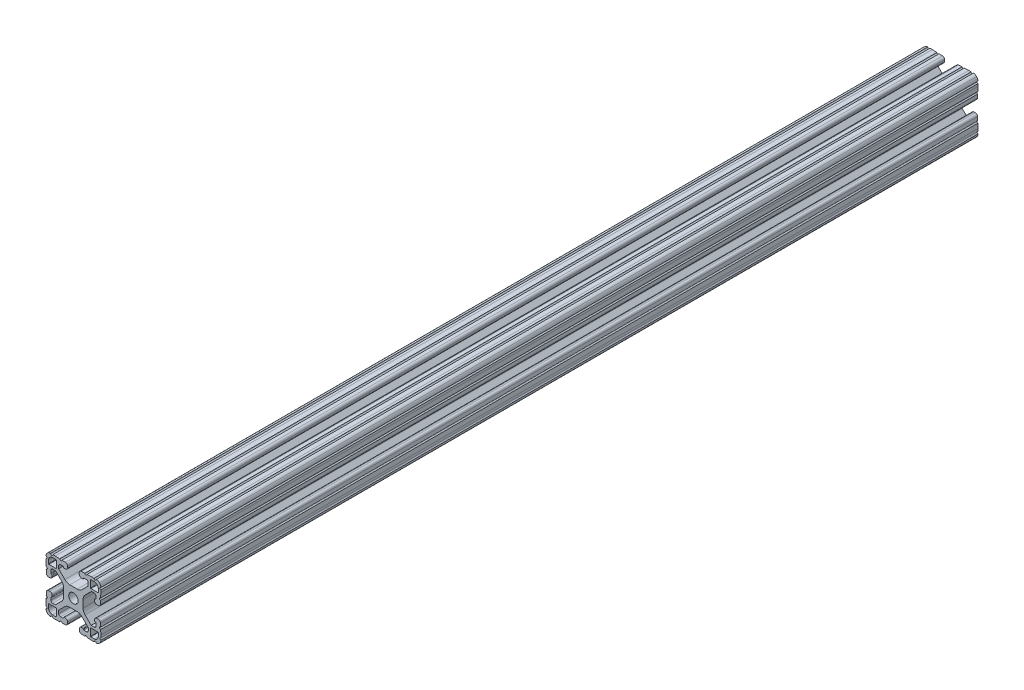
SolidWorks part; units mm, degrees
ref_plane "Front Plane" through (0, 0, 0) normal (0, 0, 1) x (1, 0, 0)
ref_plane "Top Plane" through (0, 0, 0) normal (0, 1, 0) x (1, 0, 0)
ref_plane "Right Plane" through (0, 0, 0) normal (1, 0, 0) x (0, 0, -1)
ref_plane "Plane1" through (0, 0, -25.4) normal (0, 0, -1) x (-1, 0, 0)
sketch "Sketch1" plane through (0, 0, -25.4) normal (0, 0, -1) x (-1, 0, 0)
  line L0 (-83.3577, 88.2941) -> (-83.3577, 93.1709)
  line L1 (-83.1037, 93.4249) -> (-80.767, 93.4249)
  line L2 (-77.9729, 90.6309) -> (-77.9729, 88.2941)
  line L3 (-78.2269, 88.0401) -> (-83.1037, 88.0401)
  line L4 (-83.3577, 59.2291) -> (-83.3577, 64.1059)
  line L5 (-83.1037, 64.3599) -> (-78.2269, 64.3599)
  line L6 (-77.9729, 64.1059) -> (-77.9729, 61.7691)
  line L7 (-80.767, 58.9751) -> (-83.1037, 58.9751)
  line L8 (-107.1423, 93.1709) -> (-107.1423, 88.2941)
  line L9 (-107.3963, 88.0401) -> (-112.2731, 88.0401)
  line L10 (-112.5271, 88.2941) -> (-112.5271, 90.6309)
  line L11 (-109.733, 93.4249) -> (-107.3963, 93.4249)
  line L12 (-107.1423, 64.1059) -> (-107.1423, 59.2291)
  line L13 (-107.3963, 58.9751) -> (-109.733, 58.9751)
  line L14 (-112.5271, 61.7691) -> (-112.5271, 64.1059)
  line L15 (-112.2731, 64.3599) -> (-107.3963, 64.3599)
  line L16 (-88.0437, 91.8626) -> (-86.2967, 91.9236)
  line L17 (-84.9824, 90.6544) -> (-84.9824, 88.8002)
  line L18 (-84.9824, 88.8002) -> (-89.3066, 84.476)
  line L19 (-92.7196, 83.0295) -> (-97.9616, 83.0295)
  line L20 (-101.3202, 84.4207) -> (-105.516, 88.6165)
  line L21 (-105.516, 88.6165) -> (-105.516, 90.7313)
  line L22 (-104.2017, 92.0006) -> (-102.4547, 91.9396)
  line L23 (-101.7262, 91.1059) -> (-100.9297, 91.0781)
  line L24 (-99.2999, 92.6519) -> (-99.2999, 93.5668)
  line L25 (-100.8197, 95.1407) -> (-103.2119, 95.2242)
  line L26 (-104.735, 95.2774) -> (-107.9359, 95.3892)
  line L27 (-107.9359, 95.3892) -> (-109.5615, 95.3892)
  line L28 (-114.2859, 90.6648) -> (-114.2859, 89.0392)
  line L29 (-114.2859, 89.0392) -> (-114.1741, 85.8383)
  line L30 (-114.1209, 84.3152) -> (-114.0374, 81.9231)
  line L31 (-112.4635, 80.4032) -> (-111.5486, 80.4032)
  line L32 (-109.9748, 82.033) -> (-110.0026, 82.8295)
  line L33 (-110.8377, 83.5577) -> (-110.8987, 85.3047)
  line L34 (-109.6294, 86.619) -> (-107.8072, 86.619)
  line L35 (-107.8072, 86.619) -> (-103.3649, 82.1768)
  line L36 (-101.9737, 78.8182) -> (-101.9737, 73.576)
  line L37 (-103.3649, 70.2174) -> (-107.5607, 66.0217)
  line L38 (-107.5607, 66.0217) -> (-109.6524, 66.0217)
  line L39 (-110.9217, 67.336) -> (-110.8607, 69.083)
  line L40 (-110.0322, 69.8124) -> (-110.0043, 70.6089)
  line L41 (-111.5782, 72.2387) -> (-112.4931, 72.2387)
  line L42 (-114.0669, 70.7189) -> (-114.1505, 68.3267)
  line L43 (-114.2036, 66.8036) -> (-114.3154, 63.6027)
  line L44 (-114.3154, 63.6027) -> (-114.3154, 61.9626)
  line L45 (-109.6111, 57.1437) -> (-107.9855, 57.1437)
  line L46 (-107.9855, 57.1437) -> (-104.7846, 57.2555)
  line L47 (-103.2615, 57.3086) -> (-100.8694, 57.3922)
  line L48 (-99.3495, 58.966) -> (-99.3495, 59.8809)
  line L49 (-100.9794, 61.4548) -> (-101.7758, 61.4269)
  line L50 (-102.5054, 60.599) -> (-104.2524, 60.538)
  line L51 (-105.5667, 61.8072) -> (-105.5667, 63.6295)
  line L52 (-105.5667, 63.6295) -> (-101.1311, 68.065)
  line L53 (-97.7725, 69.4562) -> (-92.5304, 69.4562)
  line L54 (-89.1717, 68.065) -> (-84.976, 63.8692)
  line L55 (-84.976, 63.8692) -> (-84.976, 61.7811)
  line L56 (-86.2903, 60.5118) -> (-88.0373, 60.5728)
  line L57 (-88.7596, 61.4332) -> (-89.5561, 61.461)
  line L58 (-91.1859, 59.8872) -> (-91.1859, 58.9723)
  line L59 (-89.6661, 57.3985) -> (-87.2739, 57.3149)
  line L60 (-85.7508, 57.2617) -> (-82.5499, 57.15)
  line L61 (-82.5499, 57.15) -> (-80.9244, 57.15)
  line L62 (-76.2, 61.8744) -> (-76.2, 63.4999)
  line L63 (-76.2, 63.4999) -> (-76.3117, 66.7008)
  line L64 (-76.3649, 68.2239) -> (-76.4484, 70.6161)
  line L65 (-78.0223, 72.1359) -> (-78.9372, 72.1359)
  line L66 (-80.511, 70.5061) -> (-80.4832, 69.7096)
  line L67 (-79.6552, 68.9801) -> (-79.5942, 67.2331)
  line L68 (-80.8634, 65.9188) -> (-82.6857, 65.9188)
  line L69 (-82.6857, 65.9188) -> (-87.1213, 70.3543)
  line L70 (-88.5125, 73.7128) -> (-88.5126, 78.955)
  line L71 (-87.1214, 82.3137) -> (-82.9257, 86.5095)
  line L72 (-82.9257, 86.5095) -> (-80.8375, 86.5095)
  line L73 (-79.5682, 85.1951) -> (-79.6293, 83.4482)
  line L74 (-80.4896, 82.7258) -> (-80.5175, 81.9294)
  line L75 (-78.9436, 80.2995) -> (-78.0287, 80.2995)
  line L76 (-76.4549, 81.8194) -> (-76.3713, 84.2115)
  line L77 (-76.3182, 85.7346) -> (-76.2064, 88.9355)
  line L78 (-76.2064, 88.9355) -> (-76.2064, 90.5611)
  line L79 (-80.9308, 95.2855) -> (-82.5564, 95.2855)
  line L80 (-82.5564, 95.2855) -> (-85.7573, 95.1737)
  line L81 (-87.2803, 95.1205) -> (-89.6725, 95.037)
  line L82 (-91.1924, 93.4632) -> (-91.1924, 92.5483)
  line L83 (-89.5625, 90.9744) -> (-88.7661, 91.0023)
  arc A0 (-83.3577, 93.1709) -> (-83.1037, 93.4249) centre (-83.1037, 93.1709) cw
  arc A1 (-80.767, 93.4249) -> (-77.9729, 90.6309) centre (-80.7669, 90.6309) cw
  arc A2 (-77.9729, 88.2941) -> (-78.2269, 88.0401) centre (-78.2269, 88.2941) cw
  arc A3 (-83.1037, 88.0401) -> (-83.3577, 88.2941) centre (-83.1037, 88.2941) cw
  arc A4 (-83.1037, 58.9751) -> (-83.3577, 59.2291) centre (-83.1037, 59.2291) cw
  arc A5 (-83.3577, 64.1059) -> (-83.1037, 64.3599) centre (-83.1037, 64.1059) cw
  arc A6 (-78.2269, 64.3599) -> (-77.9729, 64.1059) centre (-78.2269, 64.1059) cw
  arc A7 (-77.9729, 61.7691) -> (-80.767, 58.9751) centre (-80.7669, 61.7691) cw
  arc A8 (-107.3963, 93.4249) -> (-107.1423, 93.1709) centre (-107.3963, 93.1709) cw
  arc A9 (-107.1423, 88.2941) -> (-107.3963, 88.0401) centre (-107.3963, 88.2941) cw
  arc A10 (-112.2731, 88.0401) -> (-112.5271, 88.2941) centre (-112.2731, 88.2941) cw
  arc A11 (-112.5271, 90.6309) -> (-109.733, 93.4249) centre (-109.7331, 90.6309) cw
  arc A12 (-107.1423, 59.2291) -> (-107.3963, 58.9751) centre (-107.3963, 59.2291) cw
  arc A13 (-109.733, 58.9751) -> (-112.5271, 61.7691) centre (-109.7331, 61.7691) cw
  arc A14 (-112.5271, 64.1059) -> (-112.2731, 64.3599) centre (-112.2731, 64.1059) cw
  arc A15 (-107.3963, 64.3599) -> (-107.1423, 64.1059) centre (-107.3963, 64.1059) cw
  circle A16 centre (-95.25, 76.2) radius 3.2639
  arc A17 (-88.7661, 91.0023) -> (-88.3984, 91.383) centre (-88.7794, 91.383) ccw
  arc A18 (-88.3984, 91.383) -> (-88.0437, 91.8626) centre (-88.0304, 91.4819) cw
  arc A19 (-86.2967, 91.9236) -> (-84.9824, 90.6544) centre (-86.2524, 90.6544) cw
  arc A20 (-89.3066, 84.476) -> (-92.7196, 83.0295) centre (-92.7196, 87.7793) cw
  arc A21 (-97.9616, 83.0295) -> (-101.3202, 84.4207) centre (-97.9616, 87.7793) cw
  arc A22 (-105.516, 90.7313) -> (-104.2017, 92.0006) centre (-104.246, 90.7313) cw
  arc A23 (-102.4547, 91.9396) -> (-102.087, 91.5588) centre (-102.468, 91.5588) cw
  arc A24 (-102.087, 91.5588) -> (-101.7262, 91.1059) centre (-101.7129, 91.4867) ccw
  arc A25 (-100.9297, 91.0781) -> (-99.2999, 92.6519) centre (-100.8747, 92.6519) ccw
  arc A26 (-99.2999, 93.5668) -> (-100.8197, 95.1407) centre (-100.8747, 93.5668) ccw
  arc A27 (-103.2119, 95.2242) -> (-104.735, 95.2774) centre (-103.9735, 95.2508) cw
  arc A28 (-109.5615, 95.3892) -> (-111.0855, 95.3892) centre (-110.3235, 95.3892) cw
  arc A29 (-111.0855, 95.3892) -> (-113.3432, 94.4465) centre (-111.0855, 92.2142) ccw
  arc A30 (-113.3432, 94.4465) -> (-114.2859, 92.1888) centre (-111.1109, 92.1888) ccw
  arc A31 (-114.2859, 92.1888) -> (-114.2859, 90.6648) centre (-114.2859, 91.4268) cw
  arc A32 (-114.1741, 85.8383) -> (-114.1209, 84.3152) centre (-114.1475, 85.0768) cw
  arc A33 (-114.0374, 81.9231) -> (-112.4635, 80.4032) centre (-112.4635, 81.978) ccw
  arc A34 (-111.5486, 80.4032) -> (-109.9748, 82.033) centre (-111.5486, 81.978) ccw
  arc A35 (-110.0026, 82.8295) -> (-110.3834, 83.1972) centre (-110.3834, 82.8162) ccw
  arc A36 (-110.3834, 83.1972) -> (-110.8377, 83.5577) centre (-110.4569, 83.571) cw
  arc A37 (-110.8987, 85.3047) -> (-109.6294, 86.619) centre (-109.6294, 85.349) cw
  arc A38 (-103.3649, 82.1768) -> (-101.9737, 78.8182) centre (-106.7235, 78.8182) cw
  arc A39 (-101.9737, 73.576) -> (-103.3649, 70.2174) centre (-106.7235, 73.576) cw
  arc A40 (-109.6524, 66.0217) -> (-110.9217, 67.336) centre (-109.6524, 67.2917) cw
  arc A41 (-110.8607, 69.083) -> (-110.4799, 69.4507) centre (-110.4799, 69.0697) cw
  arc A42 (-110.4799, 69.4507) -> (-110.0322, 69.8124) centre (-110.413, 69.8257) ccw
  arc A43 (-110.0043, 70.6089) -> (-111.5782, 72.2387) centre (-111.5782, 70.6639) ccw
  arc A44 (-112.4931, 72.2387) -> (-114.0669, 70.7189) centre (-112.4931, 70.6639) ccw
  arc A45 (-114.1505, 68.3267) -> (-114.2036, 66.8036) centre (-114.1771, 67.5652) cw
  arc A46 (-114.3154, 61.9626) -> (-114.3332, 60.4644) centre (-114.4639, 61.2152) cw
  arc A47 (-114.3332, 60.4644) -> (-113.3928, 58.0864) centre (-111.1605, 60.3441) ccw
  arc A48 (-113.3928, 58.0864) -> (-111.1351, 57.1437) centre (-111.1351, 60.3187) ccw
  arc A49 (-111.1351, 57.1437) -> (-109.6111, 57.1437) centre (-110.3731, 57.1437) cw
  arc A50 (-104.7846, 57.2555) -> (-103.2615, 57.3086) centre (-104.0231, 57.2821) cw
  arc A51 (-100.8694, 57.3922) -> (-99.3495, 58.966) centre (-100.9243, 58.966) ccw
  arc A52 (-99.3495, 59.8809) -> (-100.9794, 61.4548) centre (-100.9243, 59.8809) ccw
  arc A53 (-101.7758, 61.4269) -> (-102.1435, 61.0462) centre (-101.7625, 61.0462) ccw
  arc A54 (-102.1435, 61.0462) -> (-102.5054, 60.599) centre (-102.5187, 60.9797) cw
  arc A55 (-104.2524, 60.538) -> (-105.5667, 61.8072) centre (-104.2967, 61.8072) cw
  arc A56 (-101.1311, 68.065) -> (-97.7725, 69.4562) centre (-97.7725, 64.7064) cw
  arc A57 (-92.5304, 69.4562) -> (-89.1717, 68.065) centre (-92.5304, 64.7064) cw
  arc A58 (-84.976, 61.7811) -> (-86.2903, 60.5118) centre (-86.246, 61.7811) cw
  arc A59 (-88.0373, 60.5728) -> (-88.405, 60.9536) centre (-88.024, 60.9536) cw
  arc A60 (-88.405, 60.9536) -> (-88.7596, 61.4332) centre (-88.7729, 61.0524) ccw
  arc A61 (-89.5561, 61.461) -> (-91.1859, 59.8872) centre (-89.6111, 59.8872) ccw
  arc A62 (-91.1859, 58.9723) -> (-89.6661, 57.3985) centre (-89.6111, 58.9723) ccw
  arc A63 (-87.2739, 57.3149) -> (-85.7508, 57.2617) centre (-86.5124, 57.2883) cw
  arc A64 (-80.9244, 57.15) -> (-79.4004, 57.15) centre (-80.1624, 57.15) cw
  arc A65 (-79.4004, 57.15) -> (-77.1426, 58.0927) centre (-79.4004, 60.325) ccw
  arc A66 (-77.1426, 58.0927) -> (-76.2, 60.3504) centre (-79.375, 60.3504) ccw
  arc A67 (-76.2, 60.3504) -> (-76.2, 61.8744) centre (-76.2, 61.1124) cw
  arc A68 (-76.3117, 66.7008) -> (-76.3649, 68.2239) centre (-76.3383, 67.4624) cw
  arc A69 (-76.4484, 70.6161) -> (-78.0223, 72.1359) centre (-78.0223, 70.5611) ccw
  arc A70 (-78.9372, 72.1359) -> (-80.511, 70.5061) centre (-78.9372, 70.5611) ccw
  arc A71 (-80.4832, 69.7096) -> (-80.1024, 69.342) centre (-80.1024, 69.723) ccw
  arc A72 (-80.1024, 69.342) -> (-79.6552, 68.9801) centre (-80.036, 68.9668) cw
  arc A73 (-79.5942, 67.2331) -> (-80.8634, 65.9188) centre (-80.8634, 67.1888) cw
  arc A74 (-87.1213, 70.3543) -> (-88.5125, 73.7128) centre (-83.7627, 73.7129) cw
  arc A75 (-88.5126, 78.955) -> (-87.1214, 82.3137) centre (-83.7628, 78.9551) cw
  arc A76 (-80.8375, 86.5095) -> (-79.5682, 85.1951) centre (-80.8375, 85.2395) cw
  arc A77 (-79.6293, 83.4482) -> (-80.01, 83.0805) centre (-80.01, 83.4615) cw
  arc A78 (-80.01, 83.0805) -> (-80.4896, 82.7258) centre (-80.1089, 82.7125) ccw
  arc A79 (-80.5175, 81.9294) -> (-78.9436, 80.2995) centre (-78.9436, 81.8743) ccw
  arc A80 (-78.0287, 80.2995) -> (-76.4549, 81.8194) centre (-78.0287, 81.8743) ccw
  arc A81 (-76.3713, 84.2115) -> (-76.3182, 85.7346) centre (-76.3448, 84.9731) cw
  arc A82 (-76.2064, 90.5611) -> (-76.2064, 92.0851) centre (-76.2064, 91.3231) cw
  arc A83 (-76.2064, 92.0851) -> (-77.1491, 94.3428) centre (-79.3814, 92.0851) ccw
  arc A84 (-77.1491, 94.3428) -> (-79.4068, 95.2855) centre (-79.4068, 92.1105) ccw
  arc A85 (-79.4068, 95.2855) -> (-80.9308, 95.2855) centre (-80.1688, 95.2855) cw
  arc A86 (-85.7573, 95.1737) -> (-87.2803, 95.1205) centre (-86.5188, 95.1471) cw
  arc A87 (-89.6725, 95.037) -> (-91.1924, 93.4632) centre (-89.6176, 93.4632) ccw
  arc A88 (-91.1924, 92.5483) -> (-89.5625, 90.9744) centre (-89.6176, 92.5483) ccw
extrude "Boss-Extrude1" add sketch "Sketch1" against normal blind 609.6
